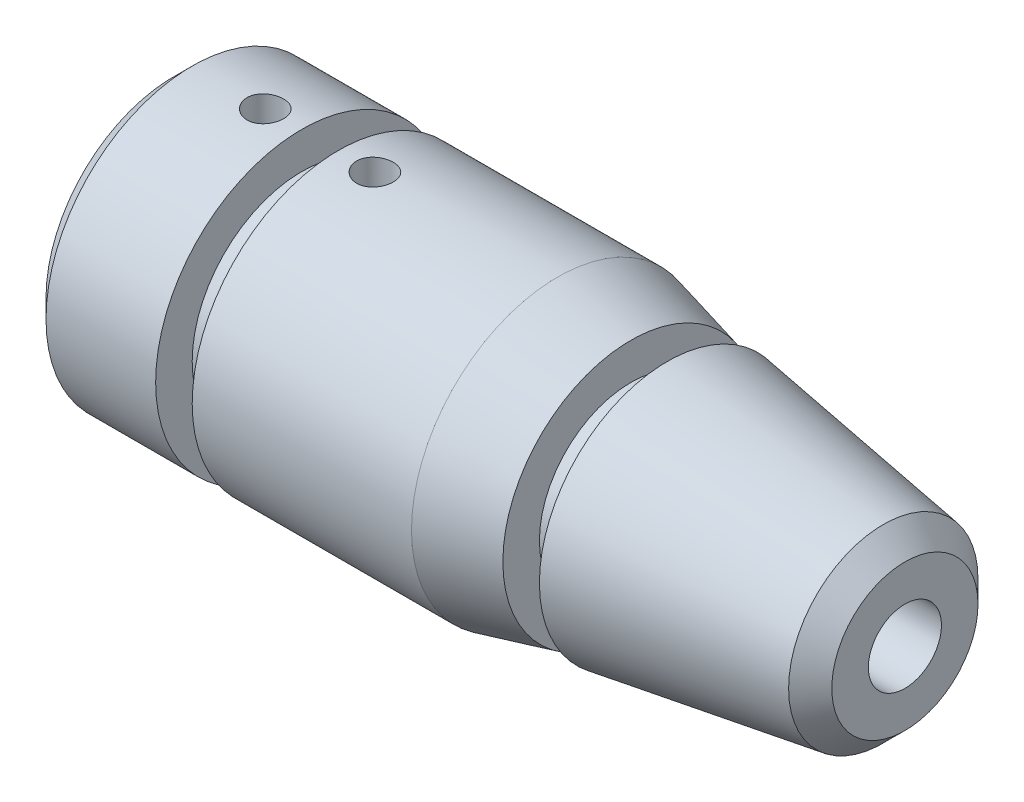
SolidWorks part; units mm, degrees
material "Manganese Bronze"
ref_plane "Front Plane" through (0, 0, 0) normal (0, 0, 1) x (1, 0, 0)
ref_plane "Top Plane" through (0, 0, 0) normal (0, 1, 0) x (1, 0, 0)
ref_plane "Right Plane" through (0, 0, 0) normal (1, 0, 0) x (0, 0, -1)
sketch "Sketch1" plane through (0, 0, 0) normal (0, 0, 1) x (1, 0, 0)
  line L0 (0, 21.9067) -> (0, 12.7)
  line L1 (0, -55) -> (0, 55) construction
  line L2 (0, 12.7) -> (11.1125, 12.7)
  line L3 (11.1125, 12.7) -> (11.1125, 9.525)
  line L4 (11.1125, 9.525) -> (14.2875, 9.525)
  line L5 (14.2875, 9.525) -> (14.2875, 12.7)
  line L6 (14.2875, 12.7) -> (33.3375, 12.7)
  line L7 (33.3375, 12.7) -> (39.6875, 11.1125)
  line L8 (39.6875, 11.1125) -> (39.6875, 7.9375)
  line L9 (39.6875, 7.9375) -> (42.8625, 7.9375)
  line L10 (42.8625, 7.9375) -> (42.8625, 11.1125)
  line L11 (42.8625, 11.1125) -> (63.5, 7.9375)
  line L12 (63.5, 7.9375) -> (63.5, 3.175)
  line L13 (63.5, 3.175) -> (25.4, 3.175)
  line L14 (25.4, 3.175) -> (20.6375, 6.35)
  line L15 (20.6375, 6.35) -> (0, 6.35)
  line L16 (0, 6.35) -> (0, 12.7)
  line L17 (55, 0) -> (-55, 0) construction
  line L18 (0, 0) -> (66.6553, 0) construction
  point P29 (42.8625, 9.525)
  dimension "D1" = 3.175
  dimension "D2" = 7.9375
  dimension "D3" = 11.1125
  dimension "D4" = 63.5
  dimension "D5" = 6.35
  dimension "D6" = 20.6375
  dimension "D7" = 25.4
  dimension "D8" = 11.1125
  dimension "D9" = 3.175
  dimension "D10" = 33.3375
  dimension "D11" = 39.6875
  dimension "D12" = 9.525
  dimension "D13" = 12.7
  dimension "D14" = 7.9375
  dimension "D15" = 3.175
revolve "Revolve1" add sketch "Sketch1" angle 360 about L18
chamfer "Chamfer1" distance 1.5875 angle 45 2 edges at (0, 0, 12.7) (63.5, 0, 7.9375)
ref_plane "Plane1" through (0, 12.7, 0) normal (0, 1, 0) x (1, 0, 0)
sketch "Sketch2" plane through (0, 12.7, 0) normal (0, 1, 0) x (1, 0, 0)
  line L0 (-13.97, 0) -> (13.97, 0) construction
  circle A0 centre (7.9375, 0) radius 1.5875
  circle A1 centre (17.4625, 0) radius 1.5875
  dimension "D1" = 3.175
  dimension "D2" = 3.175
  dimension "D3" = 7.9375
  dimension "D4" = 9.525
extrude "Cut-Extrude1" cut sketch "Sketch2" against normal up to next
